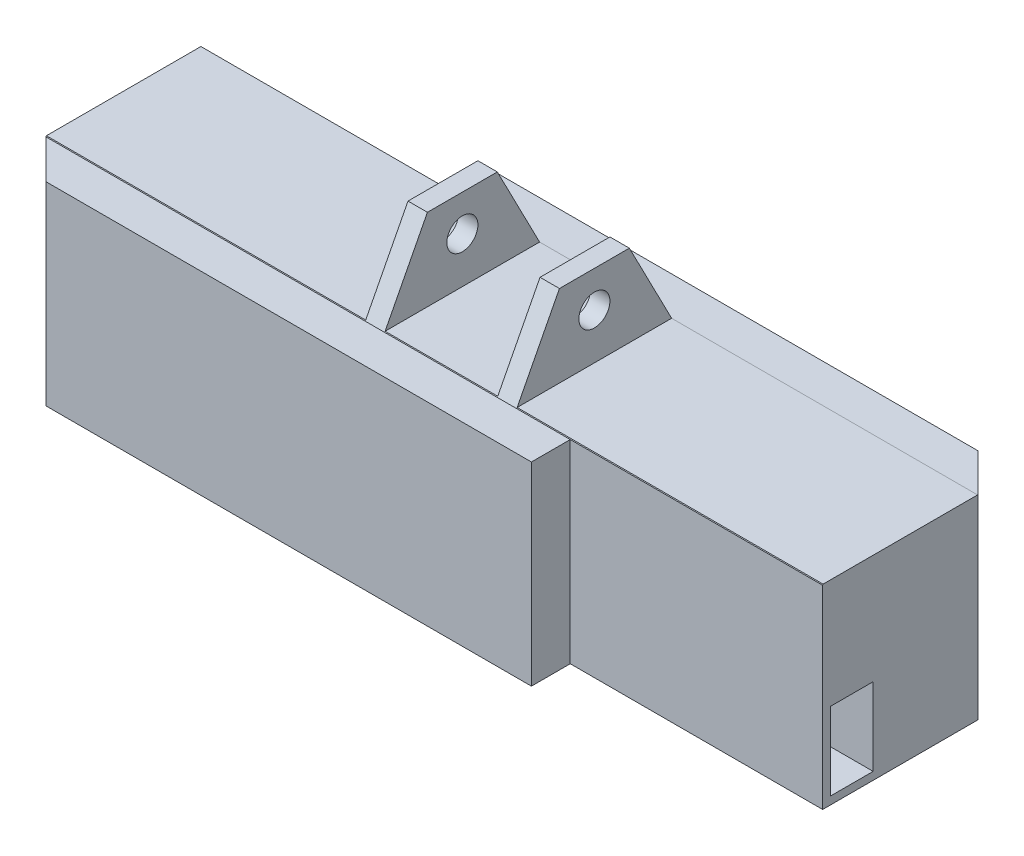
SolidWorks part; units mm, degrees
other "Markup1"
sketch "Sketch3" plane through (4953, 1016, 0) normal (0.205, 0.8966, 0.3924) x (0.9773, -0.2091, -0.0329)
ref_plane "Front Plane" through (0, 0, 0) normal (0, 0, 1) x (1, 0, 0)
ref_plane "Top Plane" through (0, 0, 0) normal (0, 1, 0) x (1, 0, 0)
ref_plane "Right Plane" through (0, 0, 0) normal (1, 0, 0) x (0, 0, -1)
sketch "Sketch1" plane through (0, 0, 0) normal (0, 1, 0) x (1, 0, 0)
  line L0 (0, 254) -> (254, 0)
  line L1 (254, 0) -> (3429, 0)
  line L2 (0, 254) -> (0, 1270)
  line L3 (1651, 1524) -> (4826, 1524)
  line L4 (5080, 254) -> (5080, 1270)
  line L5 (4826, 1524) -> (5080, 1270)
  line L8 (3429, 254) -> (5080, 254) construction
  line L9 (3429, 0) -> (3429, 254)
  line L10 (1651, 1524) -> (1651, 1270)
  line L11 (0, 1270) -> (1651, 1270)
  line L12 (5080, 254) -> (3429, 254)
  line L15 (1651, 1270) -> (0, 1270) construction
  dimension "D1" = 1524
  dimension "D2" = 5080
  dimension "D3" = 254
  dimension "D4" = 254
  dimension "D5" = 254
  dimension "D6" = 254
  dimension "D7" = 254
  dimension "D8" = 1651
  dimension "D9" = 1651
extrude "Boss-Extrude1" add sketch "Sketch1" along normal blind 1270
sketch "Sketch2" plane through (5080, 0, 0) normal (1, 0, 0) x (0, 0, -1)
  line L0 (254, 0) -> (1270, 0) construction
  line L1 (304.8, 558.8) -> (584.2, 558.8)
  line L2 (304.8, 558.8) -> (304.8, 50.8)
  line L3 (304.8, 50.8) -> (584.2, 50.8)
  line L4 (584.2, 558.8) -> (584.2, 50.8)
  line L5 (254, 1270) -> (254, 0) construction
  dimension "D1" = 50.8
  dimension "D2" = 50.8
  dimension "D3" = 508
  dimension "D4" = 279.4
extrude "Cut-Extrude1" cut sketch "Sketch2" against normal blind 3048
sketch "Sketch4" plane through (0, 0, 0) normal (-1, 0, 0) x (0, 0, 1)
  line L0 (-1270, 1270) -> (-1270, 0) construction
  line L1 (-1219.2, 558.8) -> (-939.8, 558.8)
  line L2 (-1219.2, 558.8) -> (-1219.2, 50.8)
  line L3 (-1219.2, 50.8) -> (-939.8, 50.8)
  line L4 (-939.8, 558.8) -> (-939.8, 50.8)
  line L5 (-1270, 0) -> (-254, 0) construction
  dimension "D1" = 50.8
  dimension "D2" = 50.8
  dimension "D3" = 508
  dimension "D4" = 279.4
extrude "Cut-Extrude2" cut sketch "Sketch4" against normal blind 3048
sketch "Sketch5" plane through (5080, 0, 0) normal (1, 0, 0) x (0, 0, -1)
  line L0 (254, 1270) -> (533.4, 1810.9167)
  line L1 (254, 1270) -> (1270, 1270)
  line L3 (533.4, 1810.9167) -> (990.6, 1810.9167)
  line L5 (1270, 1270) -> (990.6, 1810.9167)
  line L6 (762, 1810.9167) -> (762, 1270) construction
  line L8 (254, 1270) -> (1270, 1270) construction
  line L11 (1270, 1270) -> (1270, 0) construction
  circle A0 centre (762, 1574.8) radius 101.6
  point P4 (926.5585, 1270)
  point P6 (0, 0)
  point P19 (0, 0)
  dimension "D1" = 304.8
  dimension "D2" = 228.6
  dimension "D3" = 1016
  dimension "D4" = 1016
extrude "Boss-Extrude2" add sketch "Sketch5" against normal through all
sketch "Sketch6" plane through (0, 0, 0) normal (0, 0, 1) x (1, 0, 0)
  line L0 (2583.6307, 1810.9167) -> (2583.6307, 1016) construction
  line L1 (0, 1810.9167) -> (2088.3307, 1810.9167)
  line L2 (0, 1810.9167) -> (0, 1275.3527)
  line L3 (0, 1275.3527) -> (2088.3307, 1275.3527)
  line L4 (5080, 1810.9167) -> (5080, 1275.3527)
  line L5 (2951.9307, 1810.9167) -> (2951.9307, 1275.3527)
  line L6 (2215.3307, 1810.9167) -> (2215.3307, 1275.3527)
  line L7 (2088.3307, 1810.9167) -> (2088.3307, 1275.3527)
  line L8 (3078.9307, 1810.9167) -> (3078.9307, 1275.3527)
  line L9 (2215.3307, 1810.9167) -> (2951.9307, 1810.9167)
  line L10 (2215.3307, 1275.3527) -> (2951.9307, 1275.3527)
  line L11 (3078.9307, 1275.3527) -> (5080, 1275.3527)
  line L12 (3078.9307, 1810.9167) -> (5080, 1810.9167)
  line L14 (0, 1270) -> (0, 0) construction
  point P16 (2400.5619, 1724.7159)
  point P17 (2358.459, 1471.9389)
  point P18 (0, 1016)
  point P21 (0, 0)
  dimension "D1" = 736.6
  dimension "D2" = 127
extrude "Cut-Extrude3" cut sketch "Sketch6" against normal up to next
